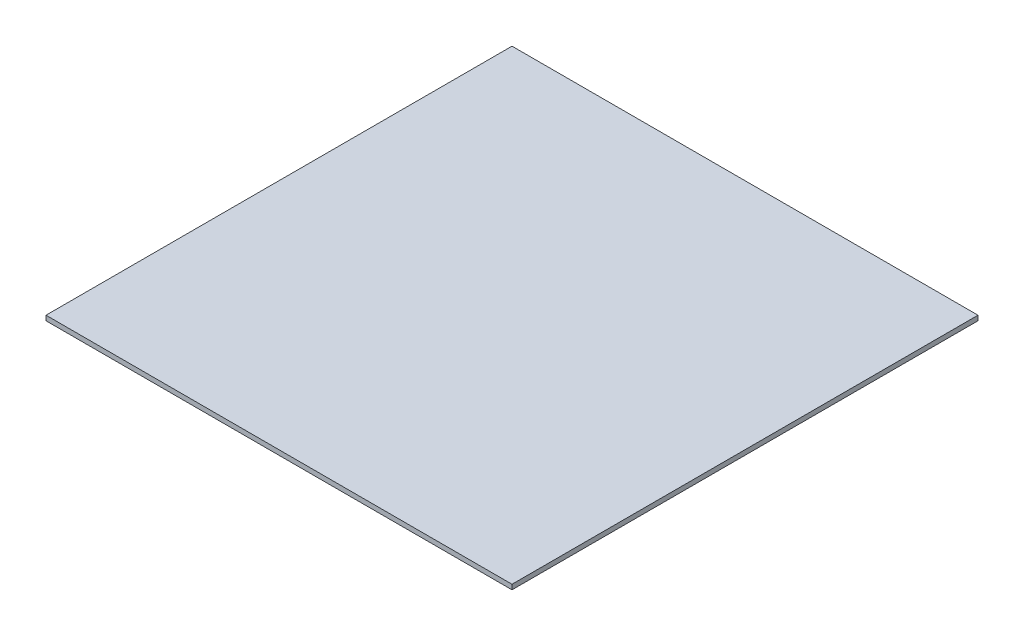
SolidWorks part; units mm, degrees
ref_plane "Front Plane" through (0, 0, 0) normal (0, 0, 1) x (1, 0, 0)
ref_plane "Top Plane" through (0, 0, 0) normal (0, 1, 0) x (1, 0, 0)
ref_plane "Right Plane" through (0, 0, 0) normal (1, 0, 0) x (0, 0, -1)
sketch "Sketch1" plane through (0, 0, 0) normal (0, 1, 0) x (1, 0, 0)
  line L1 (-304.8, -304.8) -> (304.8, -304.8)
  line L2 (-304.8, -304.8) -> (-304.8, 304.8)
  line L3 (-304.8, 304.8) -> (304.8, 304.8)
  line L4 (304.8, -304.8) -> (304.8, 304.8)
  line L5 (-304.8, -304.8) -> (304.8, 304.8) construction
  line L6 (-304.8, 304.8) -> (304.8, -304.8) construction
  point P0 (0, 0)
  dimension "D1" = 609.6
  dimension "D2" = 609.6
extrude "Boss-Extrude1" add sketch "Sketch1" along normal blind 6.35
